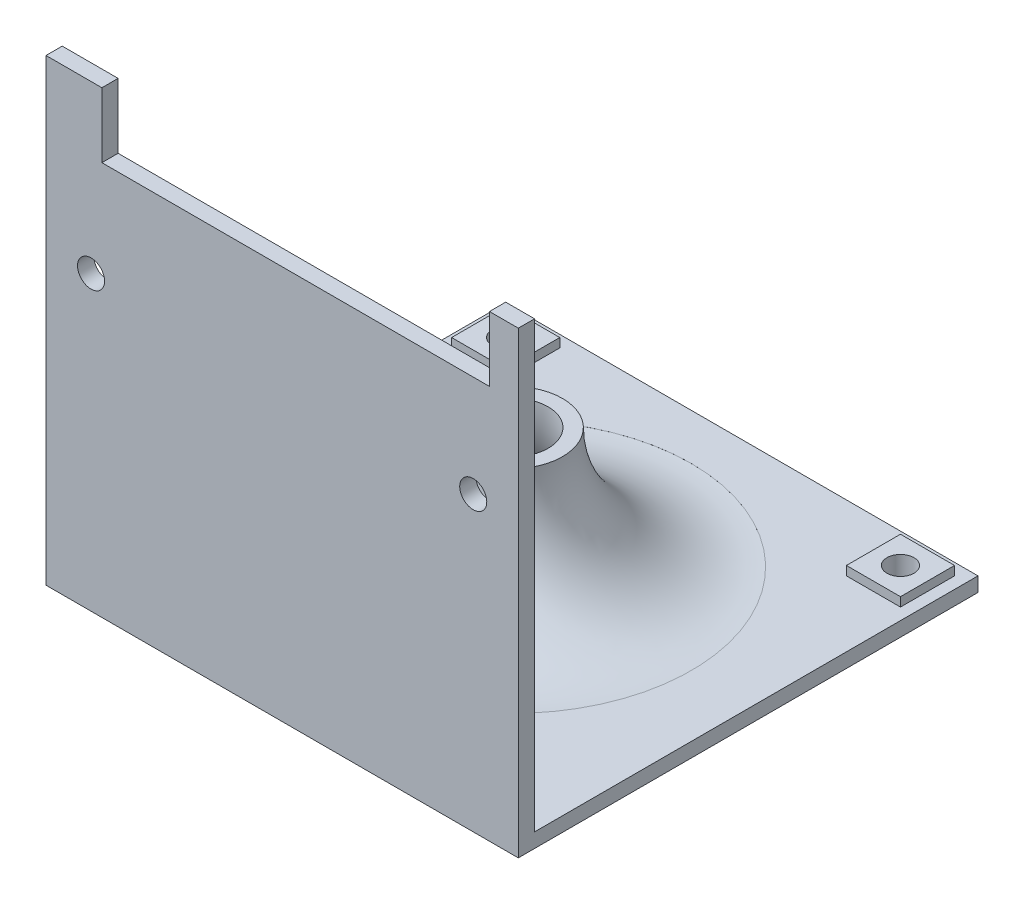
SolidWorks part; units mm, degrees
ref_plane "Front Plane" through (0, 0, 0) normal (0, 0, 1) x (1, 0, 0)
ref_plane "Top Plane" through (0, 0, 0) normal (0, 1, 0) x (1, 0, 0)
ref_plane "Right Plane" through (0, 0, 0) normal (1, 0, 0) x (0, 0, -1)
sketch "Sketch1" plane through (0, 0, 0) normal (0, 0, 1) x (1, 0, 0)
  line L0 (0, 0) -> (0, 15) construction
  line L1 (4, 0) -> (4, 15) construction
  line L2 (20, 0) -> (20, 15) construction
  line L3 (4, 15) -> (5.6, 15)
  line L4 (20, 0) -> (19.8969, 1.5967)
  arc A0 (4, 15) -> (20, 0) centre (19.0312, 15) ccw
  arc A1 (5.6, 15) -> (19.8969, 1.5967) centre (19.0312, 15) ccw
  dimension "D1" = 15
  dimension "D2" = 4
  dimension "D3" = 20
  dimension "D4" = 1.6
revolve "Revolve1" add sketch "Sketch1" angle 360 about L0
sketch "Sketch2" plane through (0, 0, 0) normal (0, 1, 0) x (1, 0, 0)
  line L1 (-25.7, 25) -> (26.7, 25)
  line L2 (-25.7, 25) -> (-25.7, -26)
  line L3 (-25.7, -26) -> (26.7, -26)
  line L4 (26.7, 25) -> (26.7, -26)
  circle A2 centre (0, 0) radius 19.8969 construction
  circle A3 centre (0, 0) radius 19.8969
  dimension "D1" = 25.7
  dimension "D2" = 25
  dimension "D3" = 51
  dimension "D4" = 52.4
extrude "Boss-Extrude1" add sketch "Sketch2" along normal blind 1.6
sketch "Sketch3" plane through (0, 1.6, 0) normal (0, 1, 0) x (1, 0, 0)
  line L0 (-25.7, 25) -> (-25.7, -26) construction
  line L1 (26.7, -26) -> (-25.7, -26)
  line L2 (26.7, -26) -> (26.7, -24.2)
  line L3 (26.7, -24.2) -> (-25.7, -24.2)
  line L4 (-25.7, -26) -> (-25.7, -24.2)
  dimension "D1" = 1.8
extrude "Boss-Extrude2" add sketch "Sketch3" along normal blind 49.3
sketch "Sketch4" plane through (0, 1.6, 0) normal (0, 1, 0) x (1, 0, 0)
  line L0 (26.7, 25) -> (-25.7, 25) construction
  line L1 (25.4, 23.7) -> (19.4, 23.7)
  line L2 (25.4, 23.7) -> (25.4, 17.7)
  line L3 (25.4, 17.7) -> (19.4, 17.7)
  line L4 (19.4, 23.7) -> (19.4, 17.7)
  line L5 (-24.4, 23.7) -> (-18.4, 23.7)
  line L6 (-24.4, 23.7) -> (-24.4, 17.7)
  line L7 (-24.4, 17.7) -> (-18.4, 17.7)
  line L8 (-18.4, 23.7) -> (-18.4, 17.7)
  line L9 (26.7, -24.2) -> (26.7, 25) construction
  line L10 (-25.7, 25) -> (-25.7, -24.2) construction
  line L11 (25.4, 23.7) -> (19.4, 17.7) construction
  dimension "D1" = 1.3
  dimension "D2" = 1.3
  dimension "D3" = 1.3
  dimension "D4" = 1.3
  dimension "D5" = 6
extrude "Boss-Extrude3" add sketch "Sketch4" along normal blind 1
sketch "Sketch5" plane through (0, 2.6, 0) normal (0, 1, 0) x (1, 0, 0)
  line L0 (25.4, 23.7) -> (19.4, 17.7) construction
  line L1 (-24.4, 23.7) -> (-18.4, 17.7) construction
  circle A0 centre (22.4, 20.7) radius 1.5
  circle A1 centre (-21.4, 20.7) radius 1.5
  dimension "D1" = 3
extrude "Cut-Extrude1" cut sketch "Sketch5" against normal through all
sketch "Sketch6" plane through (0, 0, 26) normal (0, 0, 1) x (1, 0, 0)
  line L0 (-25.7, 50.9) -> (26.7, 50.9) construction
  line L1 (23.5, 50.9) -> (-19.5, 50.9)
  line L2 (23.5, 50.9) -> (23.5, 43.7)
  line L3 (23.5, 43.7) -> (-19.5, 43.7)
  line L4 (-19.5, 50.9) -> (-19.5, 43.7)
  line L5 (26.7, 50.9) -> (26.7, 0) construction
  line L6 (-25.7, 50.9) -> (-25.7, 0) construction
  circle A0 centre (-20.7, 32.45) radius 1.5
  circle A1 centre (21.7, 32.45) radius 1.5
  dimension "D5" = 5
  dimension "D6" = 5
  dimension "D7" = 3
  dimension "D8" = 3
  dimension "D1" = 3.2
  dimension "D2" = 6.2
  dimension "D3" = 7.2
  dimension "D4" = 18.45
extrude "Cut-Extrude2" cut sketch "Sketch6" against normal through all
equation "\"D2@Sketch4\"=\"D1@Sketch4\""
equation "\"D3@Sketch4\"=\"D1@Sketch4\""
equation "\"D4@Sketch4\"=\"D1@Sketch4\""
